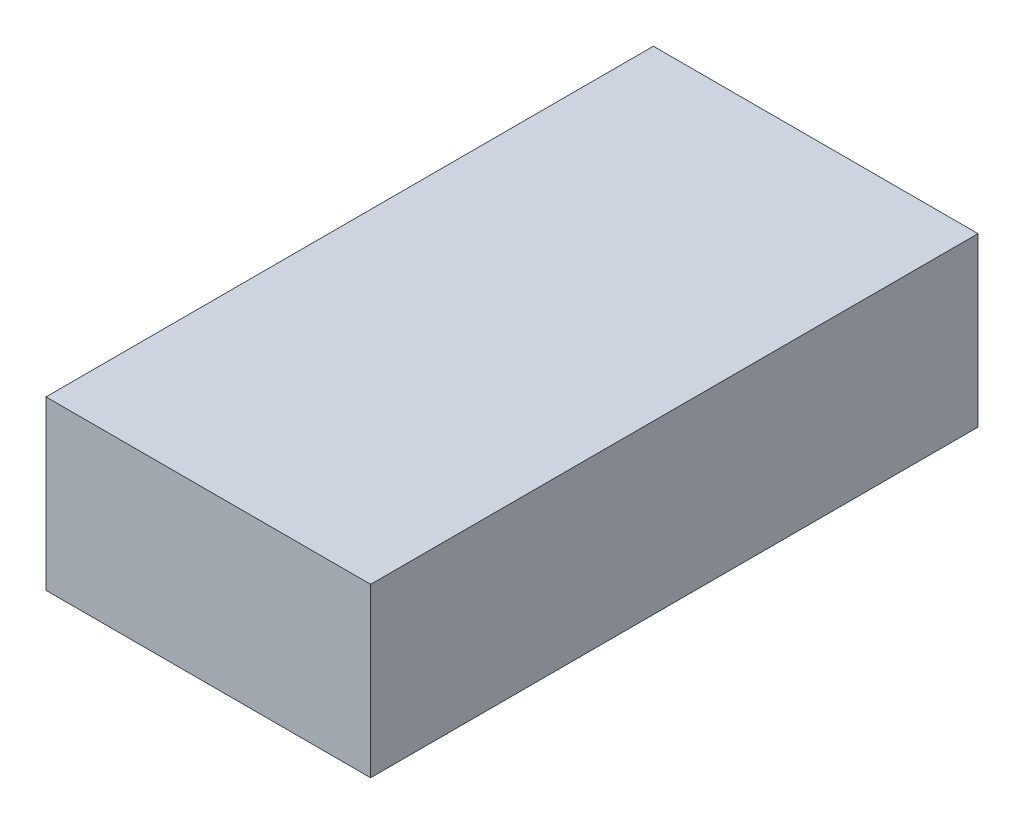
SolidWorks part; units mm, degrees
material "Custom Plastic"
ref_plane "Front Plane" through (0, 0, 0) normal (0, 0, 1) x (1, 0, 0)
ref_plane "Top Plane" through (0, 0, 0) normal (0, 1, 0) x (1, 0, 0)
ref_plane "Right Plane" through (0, 0, 0) normal (1, 0, 0) x (0, 0, -1)
sketch "Sketch2" plane through (0, 0, 0) normal (0, 1, 0) x (1, 0, 0)
  line L1 (0, 0) -> (31, 0)
  line L2 (0, 0) -> (0, -58)
  line L3 (0, -58) -> (31, -58)
  line L4 (31, 0) -> (31, -58)
  dimension "D1" = 58
  dimension "D2" = 31
extrude "Boss-Extrude1" add sketch "Sketch2" along normal blind 16
